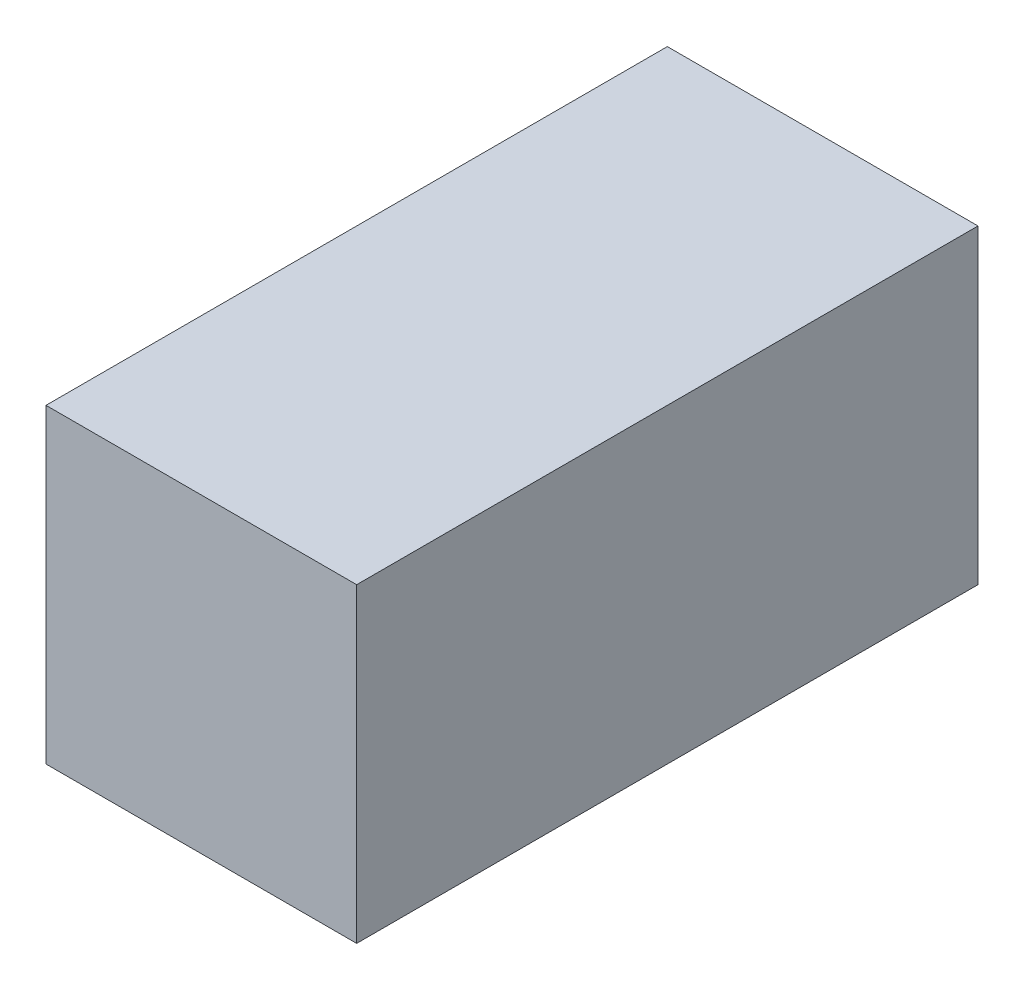
SolidWorks part; units mm, degrees
ref_plane "Front Plane" through (0, 0, 0) normal (0, 0, 1) x (1, 0, 0)
ref_plane "Top Plane" through (0, 0, 0) normal (0, 1, 0) x (1, 0, 0)
ref_plane "Right Plane" through (0, 0, 0) normal (1, 0, 0) x (0, 0, -1)
sketch "Sketch1" plane through (0, 0, 0) normal (0, 0, 1) x (1, 0, 0)
  line L1 (152.4, -152.4) -> (-152.4, -152.4)
  line L2 (152.4, -152.4) -> (152.4, 152.4)
  line L3 (152.4, 152.4) -> (-152.4, 152.4)
  line L4 (-152.4, -152.4) -> (-152.4, 152.4)
  line L5 (152.4, -152.4) -> (-152.4, 152.4) construction
  line L6 (152.4, 152.4) -> (-152.4, -152.4) construction
  point P0 (0, 0)
  dimension "D1" = 304.8
  dimension "D2" = 304.8
extrude "Boss-Extrude1" add sketch "Sketch1" along normal blind 609.6
